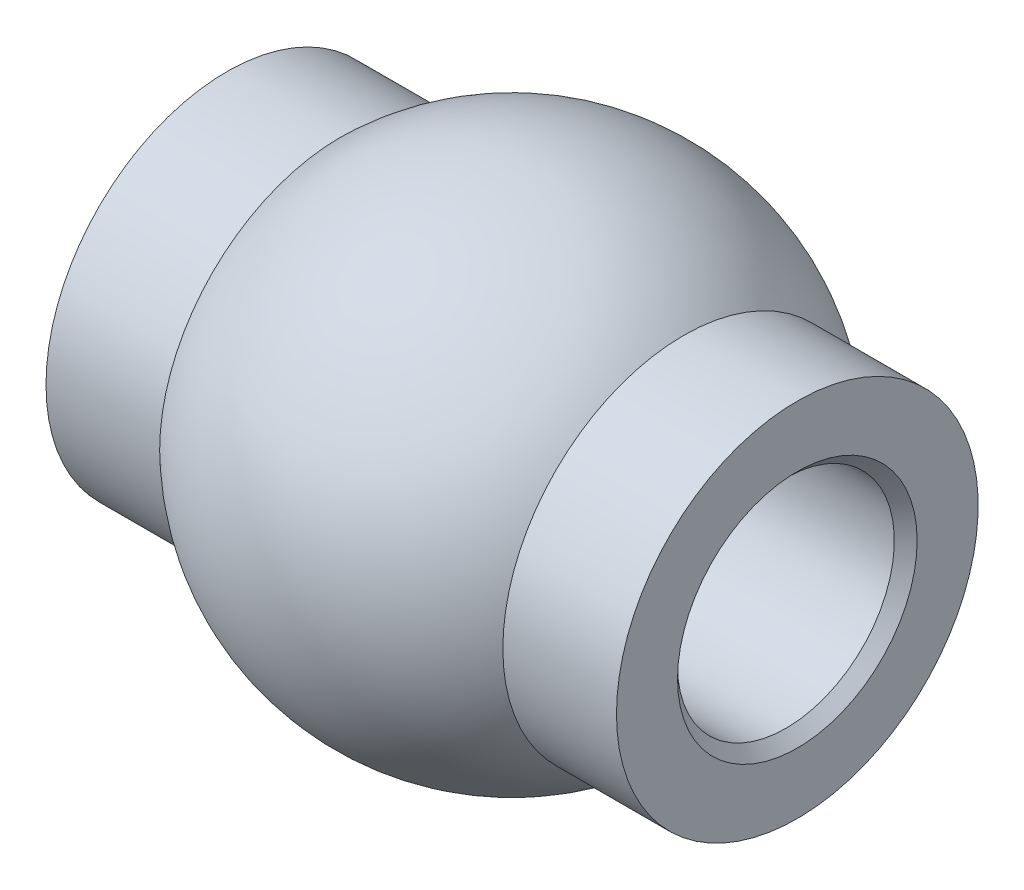
SolidWorks part; units mm, degrees
material "Alloy Steel"
ref_plane "Front Plane" through (0, 0, 0) normal (0, 0, 1) x (1, 0, 0)
ref_plane "Top Plane" through (0, 0, 0) normal (0, 1, 0) x (1, 0, 0)
ref_plane "Right Plane" through (0, 0, 0) normal (1, 0, 0) x (0, 0, -1)
sketch "Sketch1" plane through (0, 0, 0) normal (0, 0, 1) x (1, 0, 0)
  line L0 (-18.1576, 0) -> (17.6298, 0) construction
  line L1 (-6.35, 4.0259) -> (-6.35, 2.413)
  line L2 (-6.35, 4.0259) -> (-3.8201, 4.0259)
  line L3 (0, 0) -> (0, 21.5223) construction
  line L4 (6.35, 4.0259) -> (3.8201, 4.0259)
  line L5 (-6.35, 2.413) -> (6.35, 2.413)
  line L6 (6.35, 2.413) -> (6.35, 4.0259)
  arc A0 (-3.8201, 4.0259) -> (3.8201, 4.0259) centre (0, 0) cw
  point P4 (-6.35, 4.0259)
  point P10 (6.35, 4.0259)
  point P11 (-10.2773, 3.9688)
  point P12 (0, 0)
  point P13 (0, 0)
  point P14 (10.1629, 3.9688)
  point P17 (0, 0)
  dimension "D2" = 4.826
  dimension "D4" = 5.5499
  dimension "D1" = 8.0518
  dimension "D3" = 12.7
revolve "Revolve1" add sketch "Sketch1" angle 360 about L0
chamfer "Chamfer1" distance 0.254 angle 45 2 edges at (6.35, 0, 2.413) (-6.35, 0, 2.413)
